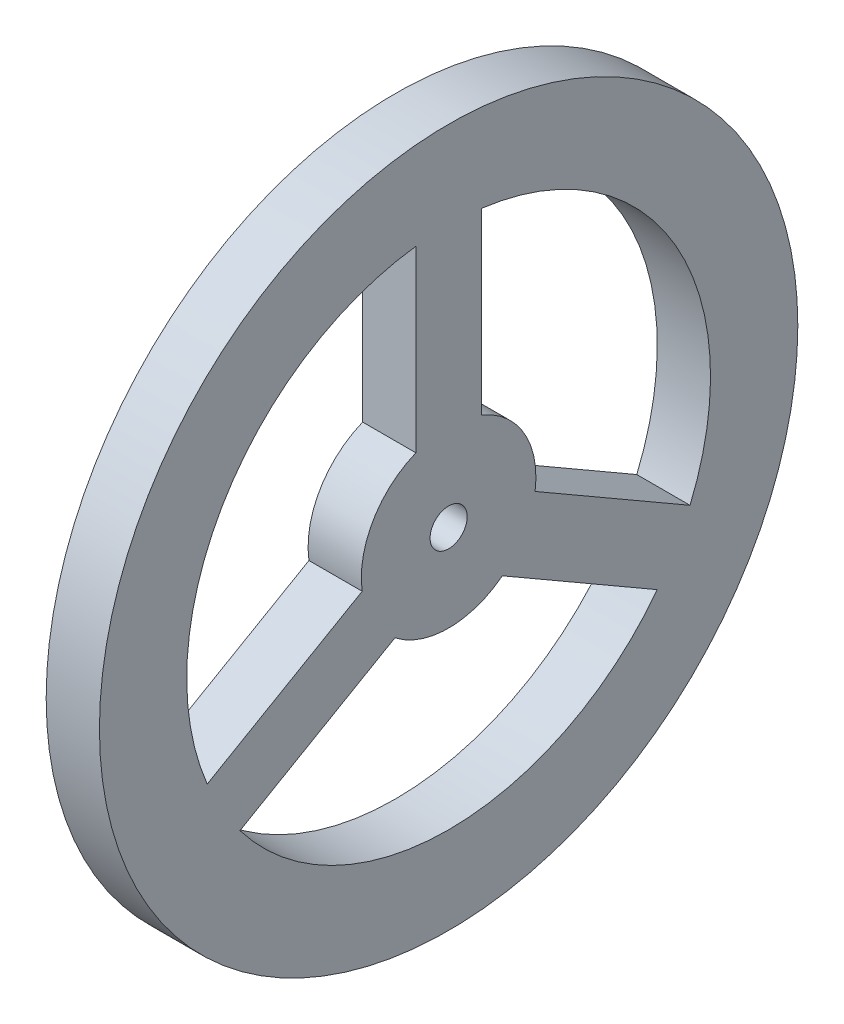
SolidWorks part; units mm, degrees
material "Corrugated Paper"
ref_plane "Front Plane" through (0, 0, 0) normal (0, 0, 1) x (1, 0, 0)
ref_plane "Top Plane" through (0, 0, 0) normal (0, 1, 0) x (1, 0, 0)
ref_plane "Right Plane" through (0, 0, 0) normal (1, 0, 0) x (0, 0, -1)
sketch "Sketch2" plane through (0, 0, 0) normal (1, 0, 0) x (0, 0, -1)
  line L0 (0, 20.32) -> (0, 0) construction
  line L1 (0, 0) -> (17.5976, -10.16) construction
  line L2 (0, 0) -> (-17.5976, -10.16) construction
  line L3 (-0.9525, -1.6498) -> (16.6451, -11.8098)
  line L4 (-0.9525, 1.6498) -> (-18.5501, -8.5102)
  line L5 (-1.905, 20.32) -> (-1.905, 0)
  line L6 (0.9525, 1.6498) -> (18.5501, -8.5102)
  line L7 (0.9525, -1.6498) -> (-16.6451, -11.8098)
  line L8 (1.905, 20.32) -> (1.905, 0)
  circle A0 centre (0, 0) radius 15.24
  circle A1 centre (0, 0) radius 20.32
  circle A2 centre (0, 0) radius 5.08
  circle A3 centre (0, 0) radius 1.0795
  dimension "D3" = 10.16
  dimension "D4" = 2.159
  dimension "D1" = 40.64
  dimension "D5" = 120
  dimension "D6" = 120
  dimension "D2" = 5.08
  dimension "D7" = 1.905
  dimension "D8" = 1.905
extrude "Boss-Extrude5" add sketch "Sketch2" along normal blind 3.0988
equation "\"rodThick\"= 0.085in"
equation "\"thick\"= 0.122in"
equation "\"D1@Boss-Extrude5\"=\"thick\""
equation "\"D4@Sketch2\"=\"rodThick\""
